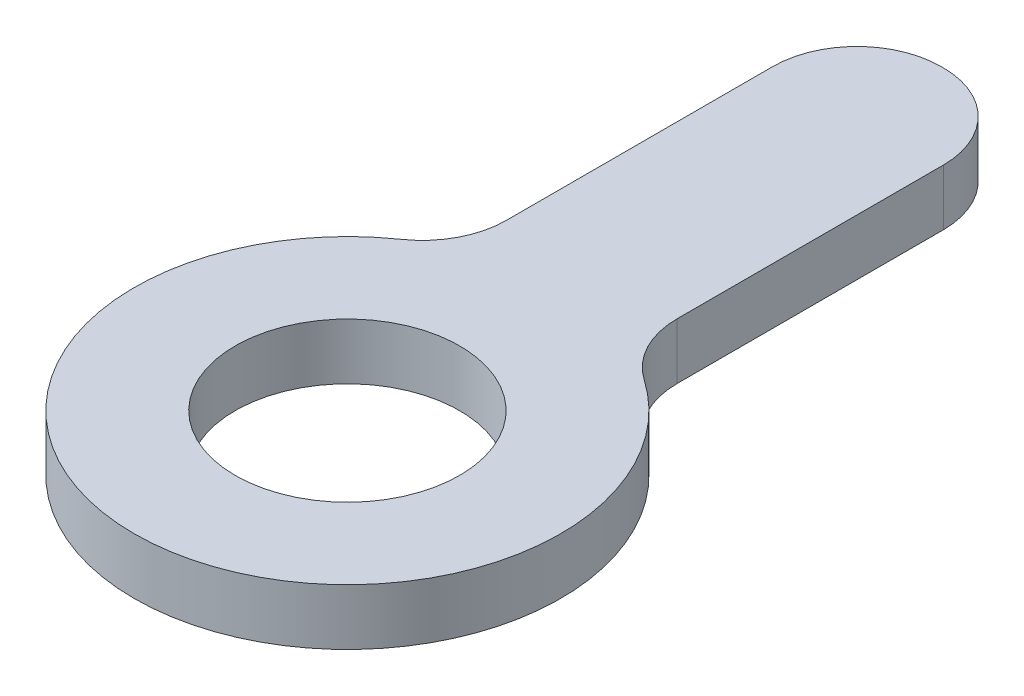
SolidWorks part; units mm, degrees
ref_plane "Front Plane" through (0, 0, 0) normal (0, 0, 1) x (1, 0, 0)
ref_plane "Top Plane" through (0, 0, 0) normal (0, 1, 0) x (1, 0, 0)
ref_plane "Right Plane" through (0, 0, 0) normal (1, 0, 0) x (0, 0, -1)
sketch "Sketch1" plane through (0, 0, 0) normal (0, 1, 0) x (1, 0, 0)
  line L0 (0, 0) -> (0, 30.8048) construction
  line L1 (4.826, 12.065) -> (4.826, 10.608)
  line L2 (-4.826, 33.655) -> (4.826, 33.655)
  line L3 (-4.826, 33.655) -> (-4.826, 12.065)
  line L4 (-4.826, 12.065) -> (4.826, 12.065)
  line L5 (4.826, 33.655) -> (4.826, 12.065)
  line L6 (4.826, 10.608) -> (-4.826, 10.608)
  line L7 (-4.826, 10.608) -> (-4.826, 12.065)
  circle A0 centre (0, 0) radius 12.065
  point P9 (0, 12.065)
  dimension "D3" = 24.13
  dimension "D1" = 21.59
  dimension "D2" = 9.652
extrude "Boss-Extrude1" add sketch "Sketch1" along normal blind 3.175
fillet "Fillet1" radius 4.7625 4 edges at (-4.826, 1.5875, -33.655) (4.826, 1.5875, -33.655) (4.826, 1.5875, -11.0578) (-4.826, 1.5875, -11.0578)
sketch "Sketch2" plane through (0, 3.175, 0) normal (0, 1, 0) x (1, 0, 0)
  circle A0 centre (0, 0) radius 6.35
  dimension "D1" = 12.7
extrude "Cut-Extrude1" cut sketch "Sketch2" against normal through all
